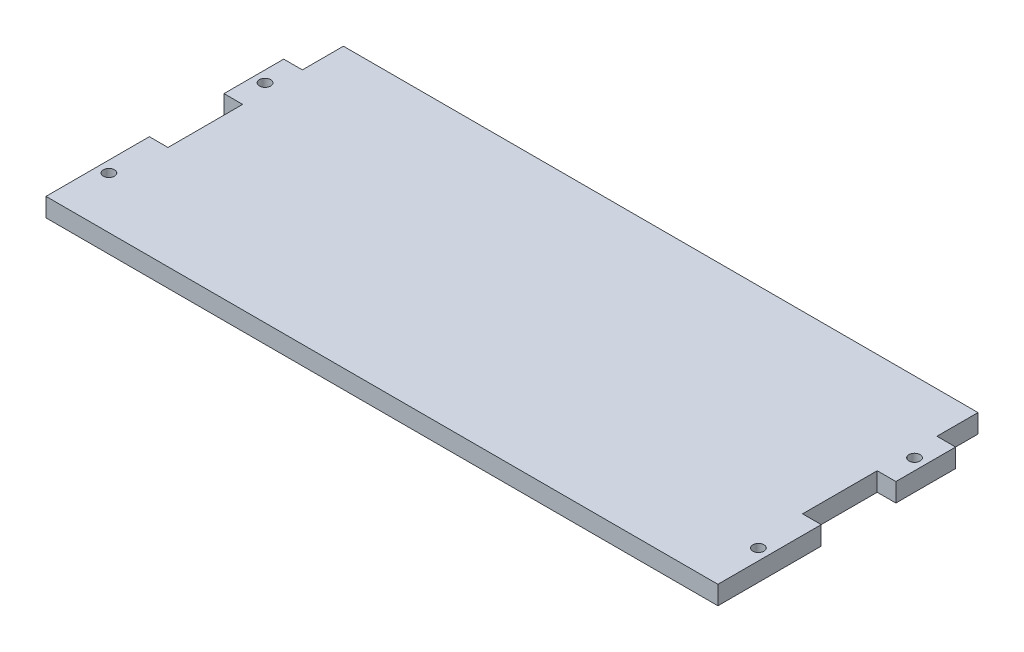
SolidWorks part; units mm, degrees
material "Trupan"
ref_plane "Alzado" through (0, 0, 0) normal (0, 0, 1) x (1, 0, 0)
ref_plane "Planta" through (0, 0, 0) normal (0, 1, 0) x (1, 0, 0)
ref_plane "Vista lateral" through (0, 0, 0) normal (1, 0, 0) x (0, 0, -1)
sketch "Croquis1" plane through (0, 0, 0) normal (0, 1, 0) x (1, 0, 0)
  line L1 (90, -8) -> (-90, -8)
  line L2 (90, -8) -> (90, 8)
  line L3 (90, 8) -> (-90, 8)
  line L4 (-90, -8) -> (-90, 8)
  line L5 (90, -8) -> (-90, 8) construction
  line L6 (90, 8) -> (-90, -8) construction
  line L7 (85, -28) -> (-85, -28)
  line L8 (85, -28) -> (85, -8)
  line L9 (85, -8) -> (-85, -8)
  line L10 (-85, -28) -> (-85, -8)
  line L11 (85, -28) -> (-85, -8) construction
  line L12 (85, -8) -> (-85, -28) construction
  line L13 (90, -55.68) -> (-90, -55.68)
  line L14 (90, -55.68) -> (90, -28)
  line L15 (90, -28) -> (-90, -28)
  line L16 (-90, -55.68) -> (-90, -28)
  line L17 (90, -55.68) -> (-90, -28) construction
  line L18 (90, -28) -> (-90, -55.68) construction
  point P0 (0, 0)
  point P6 (0, -18)
  point P11 (0, -41.84)
  point P16 (0, -8)
  dimension "D1" = 16
  dimension "D2" = 180
  dimension "D3" = 170
  dimension "D4" = 20
  dimension "D5" = 27.68
  dimension "D6" = 180
extrude "Saliente-Extruir1" add sketch "Croquis1" along normal blind 5 contours L16 L13 L14 L15 L7 | L10 L7 L8 L1 | L4 L1 L2 L3
sketch "Croquis2" plane through (0, 5, 0) normal (0, 1, 0) x (1, 0, 0)
  line L0 (-90, -8) -> (-90, 8) construction
  line L1 (-90, -55.68) -> (-90, -28) construction
  circle A0 centre (-87, 0) radius 1.5
  circle A1 centre (-87, -41.84) radius 1.5
  dimension "D1" = 3
  dimension "D2" = 3
  dimension "D3" = 3
  dimension "D4" = 3
extrude "Cortar-Extruir1" cut sketch "Croquis2" against normal through all
mirror "Simetría1" about plane through (0, 0, 0) normal (1, 0, 0) of "Cortar-Extruir1"
sketch "Croquis3" plane through (0, 5, 0) normal (0, 1, 0) x (1, 0, 0)
  line L0 (90, 8) -> (-90, 8) construction
  line L1 (85, 23) -> (-85, 23)
  line L2 (85, 23) -> (85, 8)
  line L3 (85, 8) -> (-85, 8)
  line L4 (-85, 23) -> (-85, 8)
  line L5 (85, 23) -> (-85, 8) construction
  line L6 (85, 8) -> (-85, 23) construction
  point P0 (0, 15.5)
  dimension "D1" = 170
  dimension "D2" = 15
extrude "Saliente-Extruir2" add sketch "Croquis3" against normal blind 5
sketch "Croquis5" plane through (0, 5, 0) normal (0, 1, 0) x (1, 0, 0)
  line L0 (85, 8) -> (85, 23) construction
  line L1 (-85, 23) -> (85, 23)
  line L2 (-85, 23) -> (-85, 19)
  line L3 (-85, 19) -> (85, 19)
  line L4 (85, 23) -> (85, 19)
  dimension "D1" = 4
extrude "Cortar-Extruir3" cut sketch "Croquis5" against normal through all
